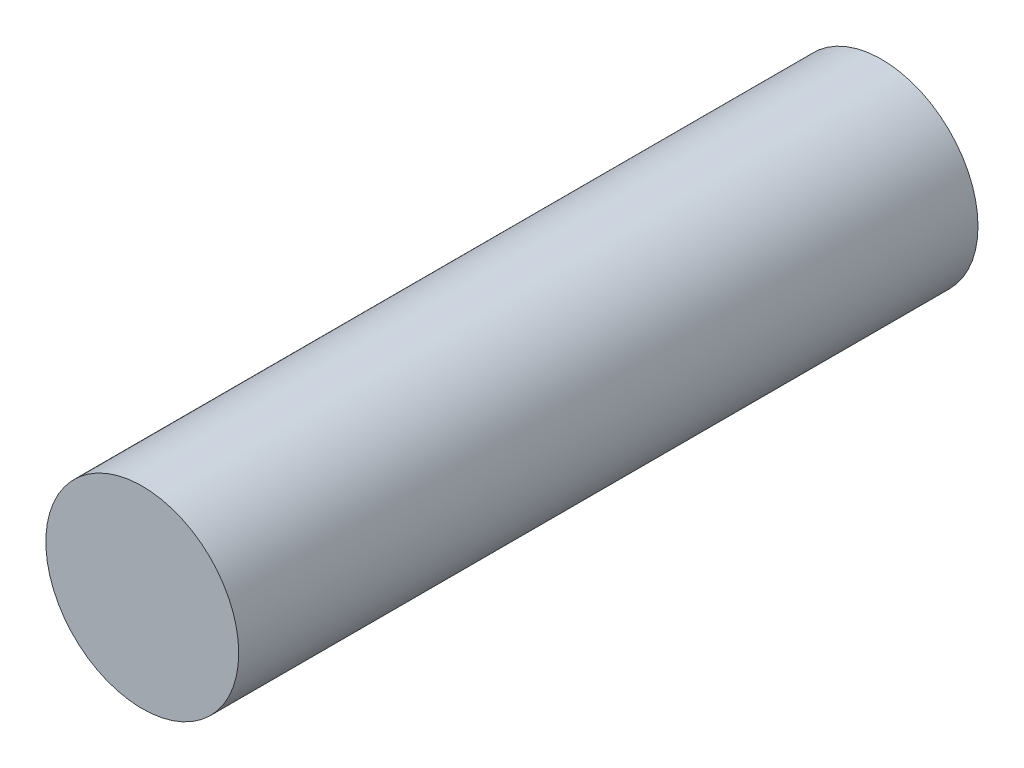
SolidWorks part; units mm, degrees
ref_plane "Front Plane" through (0, 0, 0) normal (0, 0, 1) x (1, 0, 0)
ref_plane "Top Plane" through (0, 0, 0) normal (0, 1, 0) x (1, 0, 0)
ref_plane "Right Plane" through (0, 0, 0) normal (1, 0, 0) x (0, 0, -1)
sketch "Sketch1" plane through (0, 0, 0) normal (0, 0, 1) x (1, 0, 0)
  circle A0 centre (0, 0) radius 3
  dimension "D1" = 6
extrude "Boss-Extrude1" add sketch "Sketch1" along normal blind 23
